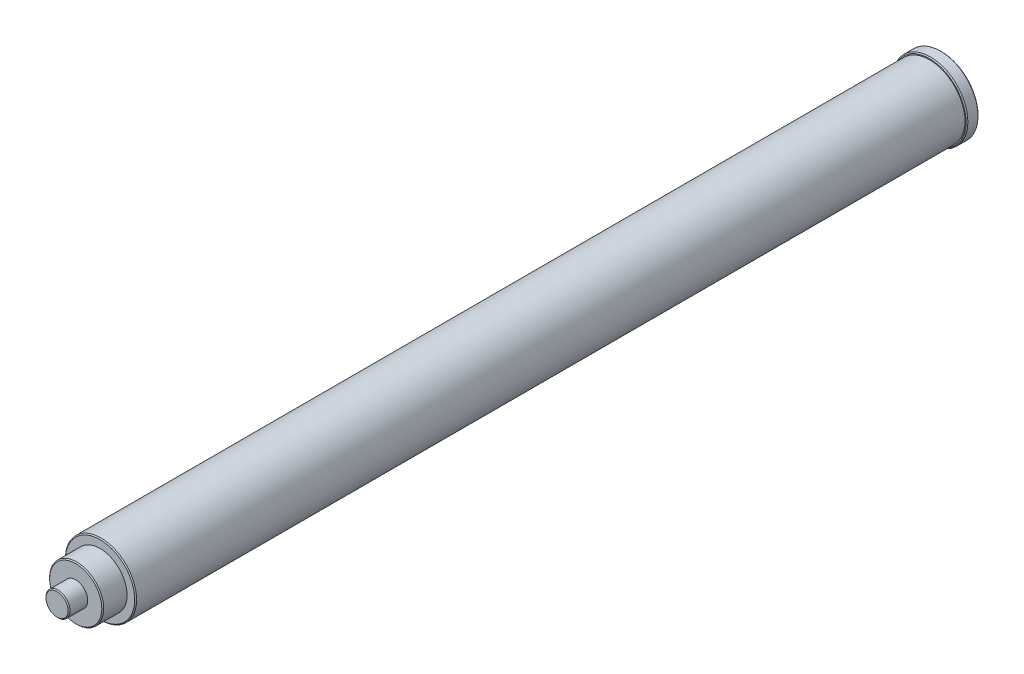
SolidWorks part; units mm, degrees
ref_plane "Front Plane" through (0, 0, 0) normal (0, 0, 1) x (1, 0, 0)
ref_plane "Top Plane" through (0, 0, 0) normal (0, 1, 0) x (1, 0, 0)
ref_plane "Right Plane" through (0, 0, 0) normal (1, 0, 0) x (0, 0, -1)
other "Center of Mass"
sketch "Sketch1" plane through (0, 0, 0) normal (0, 0, 1) x (1, 0, 0)
  circle A0 centre (0, 0) radius 39.6875
  dimension "D1" = 79.375
extrude "Boss-Extrude1" add sketch "Sketch1" along normal blind 12.7
sketch "Sketch2" plane through (0, 0, 12.7) normal (0, 0, 1) x (1, 0, 0)
  circle A0 centre (0, 0) radius 37.6555
  dimension "D1" = 75.311
extrude "Boss-Extrude2" add sketch "Sketch2" along normal blind 877.2906
sketch "Sketch3" plane through (0, 0, 889.9906) normal (0, 0, 1) x (1, 0, 0)
  circle A0 centre (0, 0) radius 28.575
  dimension "D1" = 57.15
extrude "Boss-Extrude3" add sketch "Sketch3" along normal offset from surface (25.7048 mm away) 902.9954 up to face at (37.6555, 0, 12.7) offset beyond the face yes
sketch "Sketch4" plane through (0, 0, 915.6954) normal (0, 0, 1) x (1, 0, 0)
  circle A0 centre (0, 0) radius 12.7
  dimension "D1" = 25.4
extrude "Boss-Extrude4" add sketch "Sketch4" along normal offset from surface (19.7358 mm away) 922.7312 up to face at (37.6555, 0, 12.7) offset beyond the face yes
chamfer "Chamfer1" distance 1 angle 45 5 edges at (12.7, 0, 935.4312) (39.6875, 0, 0) (39.6875, 0, 12.7) (37.6555, 0, 889.9906) (28.575, 0, 915.6954)
